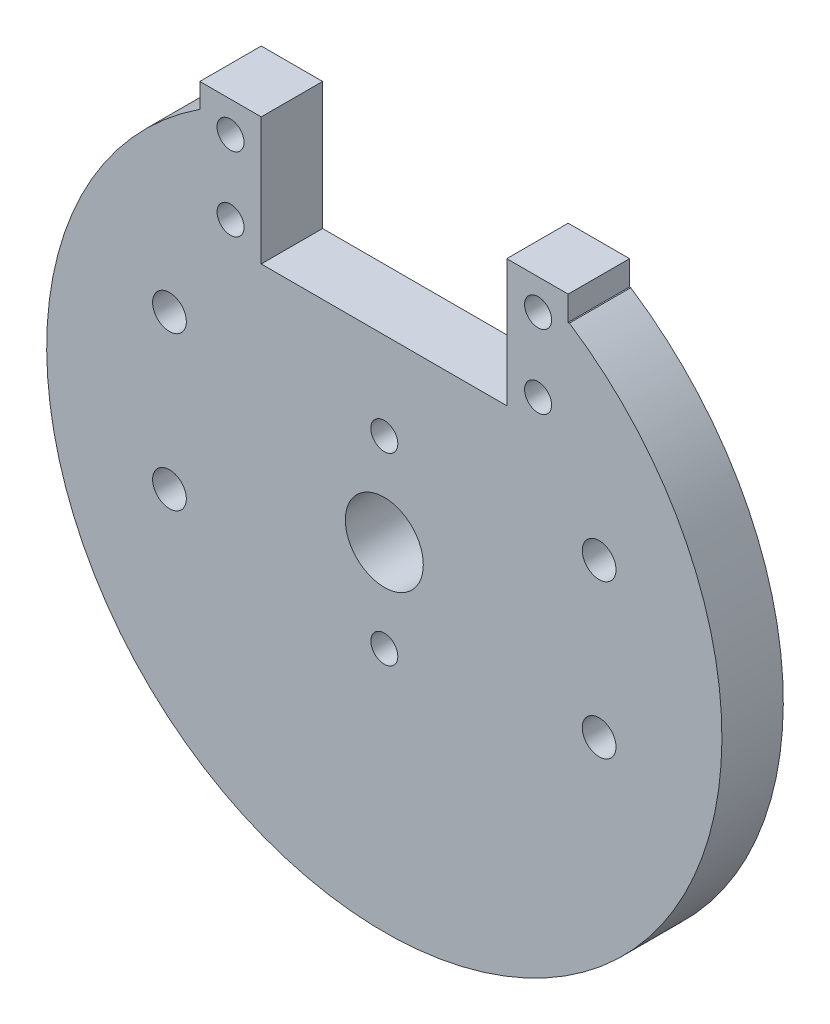
SolidWorks part; units mm, degrees
material "6061 Alloy"
ref_plane "Front Plane" through (0, 0, 0) normal (0, 0, 1) x (1, 0, 0)
ref_plane "Top Plane" through (0, 0, 0) normal (0, 1, 0) x (1, 0, 0)
ref_plane "Right Plane" through (0, 0, 0) normal (1, 0, 0) x (0, 0, -1)
sketch "Sketch1" plane through (0, 0, 0) normal (0, 0, 1) x (1, 0, 0)
  circle A0 centre (0, 0) radius 55
  dimension "D1" = 110
extrude "3/8" add sketch "Sketch1" along normal blind 10
sketch "Sketch2" plane through (0, 0, 10) normal (0, 0, 1) x (1, 0, 0)
  line L0 (0, 0) -> (0, 55) construction
  line L1 (-1.3148, 74.311) -> (0, 76.3551) construction
  line L3 (-20.0506, 46) -> (-20.0506, 29.25)
  line L4 (-20.0506, 29.25) -> (19.9494, 29.25)
  line L5 (19.9494, 46) -> (19.9494, 29.25)
  line L6 (0, 0) -> (0, 55) construction
  line L7 (-20.0506, 37.625) -> (19.9494, 37.625) construction
  line L8 (-30.1496, 76.3551) -> (30.1496, 76.3551)
  line L9 (-30.1496, 76.3551) -> (-30.1496, 46)
  line L10 (-30.1496, 46) -> (-20.0506, 46)
  line L11 (30.1496, 76.3551) -> (30.1496, 46)
  line L12 (19.9494, 46) -> (30.1496, 46)
  line L13 (-30.1496, 61.1776) -> (30.1496, 61.1776) construction
  circle A0 centre (0, 0) radius 55 construction
  point P6 (0, 37.625)
  point P130 (-0.1244, 61.1776)
  dimension "D1" = 40
  dimension "D2" = 29.25
  dimension "D3" = 46
extrude "Cut-Extrude1" cut sketch "Sketch2" against normal up to surface (10 mm away) up to face at (55, 0, 0)
sketch "Sketch3" plane through (0, 0, 10) normal (0, 0, 1) x (1, 0, 0)
  line L1 (-20.0506, 29.25) -> (-30.0506, 29.25)
  line L2 (-20.0506, 29.25) -> (-20.0506, 50)
  line L3 (-20.0506, 50) -> (-30.0506, 50)
  line L4 (-30.0506, 29.25) -> (-30.0506, 50)
  line L5 (-25.0506, 50) -> (-25.0506, 29.25) construction
  line L6 (-20.0506, 39.625) -> (-30.0506, 39.625) construction
  line L7 (19.9494, 29.25) -> (29.9494, 29.25)
  line L8 (19.9494, 29.25) -> (19.9494, 50)
  line L9 (19.9494, 50) -> (29.9494, 50)
  line L10 (29.9494, 29.25) -> (29.9494, 50)
  line L11 (24.9494, 50) -> (24.9494, 29.25) construction
  line L12 (19.9494, 39.625) -> (29.9494, 39.625) construction
  point P168 (24.9494, 39.625)
  point P204 (-25.0506, 39.625)
  dimension "D1" = 10
  dimension "D2" = 10
  dimension "D3" = 50
extrude "Boss-Extrude2" add sketch "Sketch3" against normal up to surface (10 mm away) up to face at (-0.0337, 23.5833, 0)
sketch "Sketch4" plane through (0, 0, 10) normal (0, 0, 1) x (1, 0, 0)
  line L0 (-20.0506, 39) -> (-30.0506, 39) construction
  line L2 (-30.0506, 50) -> (-30.0506, 46) construction
  line L3 (-25.0506, 45) -> (-25.0506, 39) construction
  line L4 (0, 0) -> (0, 50.3734) construction
  line L5 (-20.0506, 50) -> (-20.0506, 29.25) construction
  circle A0 centre (-25.0506, 45) radius 2.2
  circle A1 centre (-25.0506, 33) radius 2.2
  circle A2 centre (25.0506, 33) radius 2.2
  circle A3 centre (25.0506, 45) radius 2.2
  point P2 (0, 0)
  dimension "D1" = 4.4
  dimension "D2" = 6
  dimension "D3" = 39
extrude "M4_through" cut sketch "Sketch4" against normal up to surface (10 mm away) up to face at (-0.0405, 34.15, 0)
sketch "Sketch5" plane through (0, 0, 10) normal (0, 0, 1) x (1, 0, 0)
  circle A0 centre (0, 0) radius 6.35
  dimension "D1" = 12.7
extrude "Cut-Extrude2" cut sketch "Sketch5" against normal up to surface (10 mm away) up to face at (27.2506, 45, 0)
sketch "Sketch6" plane through (0, 0, 10) normal (0, 0, 1) x (1, 0, 0)
  circle A0 centre (0, 0) radius 15 construction
  circle A1 centre (0, 15) radius 2.2
  circle A2 centre (0, -15) radius 2.2
  point P13 (0, 0)
  dimension "D1" = 30
  dimension "D2" = 4.4
  dimension "D3" = 2
extrude "M4_through2" cut sketch "Sketch6" against normal up to surface (10 mm away) up to face at (6.35, 0, 0)
sketch "Sketch7" plane through (0, 0, 10) normal (0, 0, 1) x (1, 0, 0)
  line L0 (0, 0) -> (0, 38.8961) construction
  line L1 (-35, 15) -> (-35, -10) construction
  circle A0 centre (-35, 15) radius 2.75
  circle A1 centre (-35, -10) radius 2.75
  circle A2 centre (35, -10) radius 2.75
  circle A3 centre (35, 15) radius 2.75
  circle A4 centre (0, 0) radius 30 construction
  dimension "D2" = 5.5
  dimension "D3" = 25
  dimension "D4" = 60
  dimension "D1" = 35
  dimension "D5" = 15
extrude "M5_through" cut sketch "Sketch7" against normal up to surface (10 mm away) up to face at (2.2, 15, 0)
sketch "Sketch8" plane through (0, 0, 0) normal (0, 0, 1) x (1, 0, 0)
  line L0 (0, 0) -> (0, 38.8961) construction
  line L1 (-45, 10) -> (-45, -15) construction
  circle A0 centre (-45, 10) radius 2.75
  circle A3 centre (45, 10) radius 2.75
  circle A4 centre (0, 0) radius 30 construction
  dimension "D2" = 5.5
  dimension "D3" = 25
  dimension "D4" = 60
  dimension "D1" = 45
  dimension "D5" = 10
